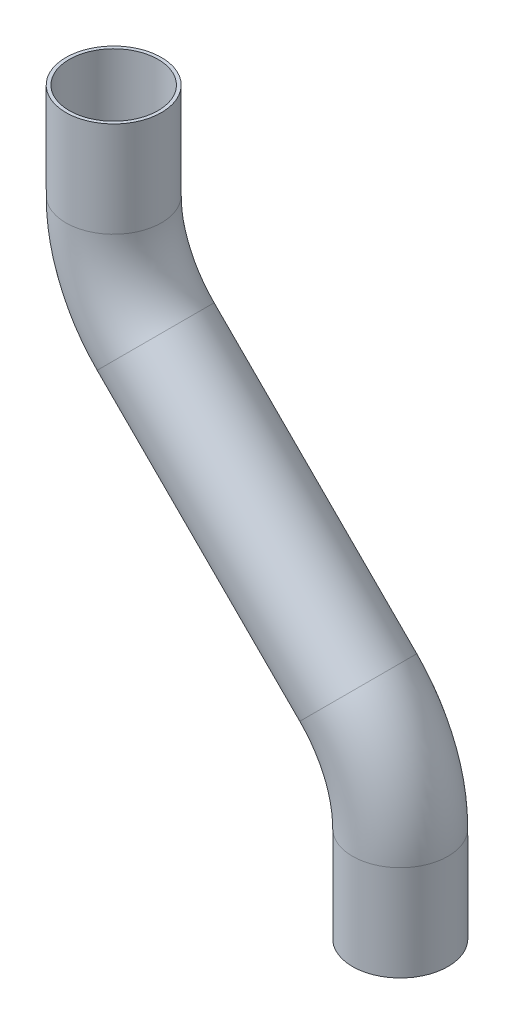
SolidWorks part; units mm, degrees
material "AISI 316 Annealed Stainless Steel Bar (SS)"
ref_plane "Front Plane" through (0, 0, 0) normal (0, 0, 1) x (1, 0, 0)
ref_plane "Top Plane" through (0, 0, 0) normal (0, 1, 0) x (1, 0, 0)
ref_plane "Right Plane" through (0, 0, 0) normal (1, 0, 0) x (0, 0, -1)
sketch "Sketch1" plane through (0, 0, 0) normal (0, 1, 0) x (1, 0, 0)
  circle A0 centre (0, 0) radius 11.811
  circle A1 centre (0, 0) radius 12.7
  dimension "D1" = 23.622
  dimension "D2" = 25.4
sketch "Sketch2" plane through (0, 0, 0) normal (0, 0, 1) x (1, 0, 0)
  line L0 (0, 0) -> (0, 25.4)
  line L1 (-11.1592, 52.3408) -> (-65.0408, 106.2223)
  line L2 (-76.2, 133.1631) -> (-76.2, 158.5631)
  arc A0 (0, 25.4) -> (-11.1592, 52.3408) centre (-38.1, 25.4) ccw
  arc A1 (-65.0408, 106.2223) -> (-76.2, 133.1631) centre (-38.1, 133.1631) cw
  point P8 (-76.2, 209.5612)
  point P10 (-76.2, 158.7335)
  dimension "D2" = 38.1
  dimension "D1" = 76.2
  dimension "D3" = 25.4
  dimension "D4" = 45
sweep "Sweep1" add profiles "Sketch1" path "Sketch2"
